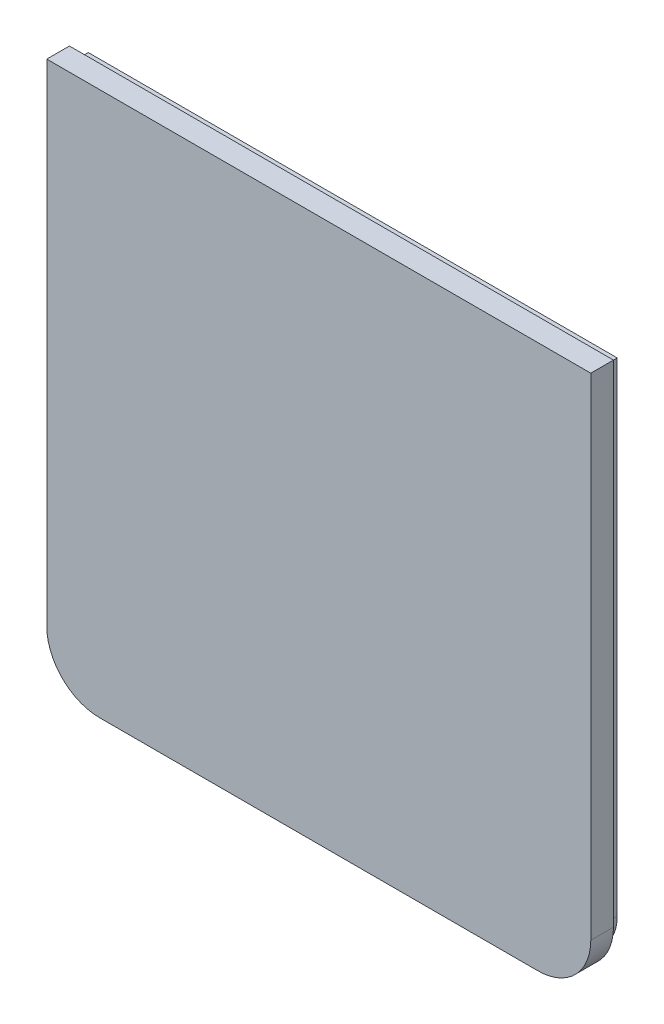
SolidWorks part; units mm, degrees
ref_plane "Front Plane" through (0, 0, 0) normal (0, 0, 1) x (1, 0, 0)
ref_plane "Top Plane" through (0, 0, 0) normal (0, 1, 0) x (1, 0, 0)
ref_plane "Right Plane" through (0, 0, 0) normal (1, 0, 0) x (0, 0, -1)
sketch "Sketch1" plane through (0, 0, 0) normal (0, 0, 1) x (1, 0, 0)
  line L5 (-58, -72) -> (58, -72)
  line L6 (-72, -58) -> (-72, 72)
  line L7 (-72, 72) -> (72, 72)
  line L8 (72, -58) -> (72, 72)
  line L9 (-72, -72) -> (72, 72) construction
  line L10 (-72, 72) -> (72, -72) construction
  arc A0 (58, -72) -> (72, -58) centre (58, -58) ccw
  arc A1 (-58, -72) -> (-72, -58) centre (-58, -58) cw
  point P0 (0, 0)
  dimension "D3" = 14
  dimension "D1" = 144
  dimension "D2" = 144
extrude "Boss-Extrude1" add sketch "Sketch1" along normal blind 6
sketch "Sketch2" plane through (0, 0, 0) normal (0, 0, -1) x (-1, 0, 0)
  line L4 (-67, 67) -> (-67, -58)
  line L5 (-58, -67) -> (58, -67)
  line L6 (67, -58) -> (67, 67)
  line L7 (67, 67) -> (-67, 67)
  line L8 (-70, 70) -> (-70, -58)
  line L9 (-58, -70) -> (58, -70)
  line L10 (70, -58) -> (70, 70)
  line L11 (70, 70) -> (-70, 70)
  line L12 (-70, 70) -> (-70, -58)
  line L13 (-58, -70) -> (58, -70)
  line L14 (70, -58) -> (70, 70)
  line L15 (70, 70) -> (-70, 70)
  arc A2 (-67, -58) -> (-58, -67) centre (-58, -58) ccw
  arc A3 (58, -67) -> (67, -58) centre (58, -58) ccw
  arc A4 (-70, -58) -> (-58, -70) centre (-58, -58) ccw
  arc A5 (58, -70) -> (70, -58) centre (58, -58) ccw
  arc A6 (-70, -58) -> (-58, -70) centre (-58, -58) ccw
  arc A7 (58, -70) -> (70, -58) centre (58, -58) ccw
  dimension "D1" = 2
  dimension "D2" = 3
extrude "Boss-Extrude2" add sketch "Sketch2" along normal blind 3
